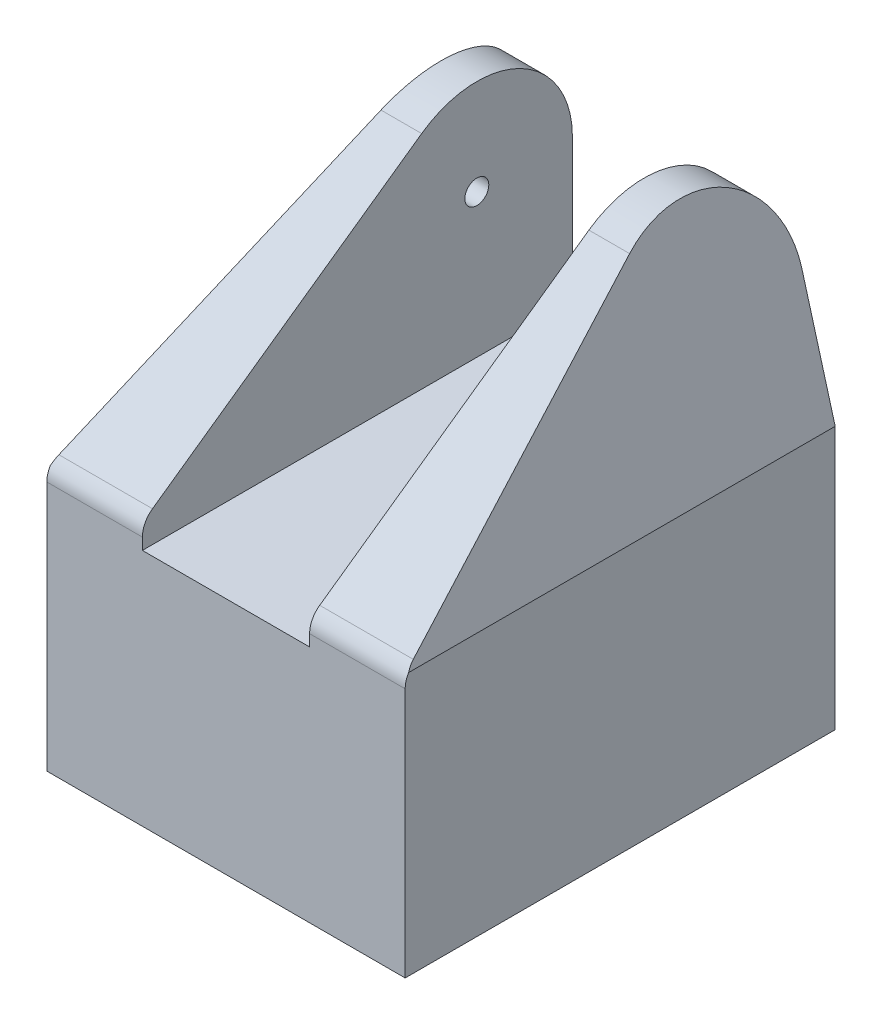
SolidWorks part; units mm, degrees
ref_plane "前基準面" through (0, 0, 0) normal (0, 0, 1) x (1, 0, 0)
ref_plane "上基準面" through (0, 0, 0) normal (0, 1, 0) x (1, 0, 0)
ref_plane "右基準面" through (0, 0, 0) normal (1, 0, 0) x (0, 0, -1)
sketch "草圖1" plane through (0, 0, 0) normal (1, 0, 0) x (0, 0, -1)
  line L4 (0, 0) -> (0, 160)
  line L5 (-63.0931, 192.6605) -> (-180, 110)
  line L6 (-180, 110) -> (-180, 0)
  line L7 (-180, 0) -> (0, 0)
  line L8 (-40, 200) -> (39.9971, 200) construction
  arc A0 (-63.0931, 192.6605) -> (0, 160) centre (-40, 160) cw
  point P7 (0, 237.2713)
  dimension "D4" = 40
  dimension "D1" = 200
  dimension "D2" = 110
  dimension "D3" = 180
extrude "填料-伸長1" add sketch "草圖1" along normal blind 150
fillet "圓角1" radius 10 1 edges at (75, 110, 180)
sketch "草圖2" plane through (0, 0, 0) normal (0, 0, -1) x (-1, 0, 0)
  line L0 (-150, 160) -> (0, 160) construction
  line L5 (-150, 110) -> (-125, 200)
  line L6 (-150, 0) -> (-150, 160) construction
  line L7 (-150, 0) -> (0, 0) construction
  line L8 (-110, 110) -> (-110, 202.9168)
  line L9 (-110, 202.9168) -> (-40, 202.9168)
  line L10 (-40, 202.9168) -> (-40, 110)
  line L11 (0, 200) -> (-150, 200) construction
  line L12 (-125, 200) -> (-125, 212.3172)
  line L13 (-125, 212.3172) -> (-176.077, 212.3172)
  line L14 (-176.077, 212.3172) -> (-176.077, 111.4072)
  line L15 (-176.077, 111.4072) -> (-150, 110)
  line L16 (-75, 160) -> (-75, 51.1238) construction
  line L17 (26.077, 111.4072) -> (0, 110)
  line L18 (26.077, 212.3172) -> (26.077, 111.4072)
  line L19 (-25, 212.3172) -> (26.077, 212.3172)
  line L20 (-25, 200) -> (-25, 212.3172)
  line L21 (0, 110) -> (-25, 200)
  line L22 (-110, 110) -> (-110, 100)
  line L23 (-110, 100) -> (-40, 100)
  line L24 (-40, 100) -> (-40, 110)
  point P0 (-75, 160)
  dimension "D1" = 70
  dimension "D2" = 100
  dimension "D3" = 15
  dimension "D4" = 35
extrude "除料-伸長1" cut sketch "草圖2" against normal through all
sketch "Sketch1" plane through (0, 0, 0) normal (0, -1, 0) x (1, 0, 0)
  line L1 (150, 0) -> (0, 0) construction
  circle A0 centre (75, 40) radius 12.5
  dimension "D2" = 25
  dimension "D1" = 40
extrude "Cut-Extrude1" cut sketch "Sketch1" against normal blind 10
sketch "Sketch2" plane through (40, 0, 0) normal (1, 0, 0) x (0, 0, -1)
  circle A0 centre (-40, 160) radius 5
extrude "Cut-Extrude2" cut sketch "Sketch2" against normal blind 10 and the other way blind 80
